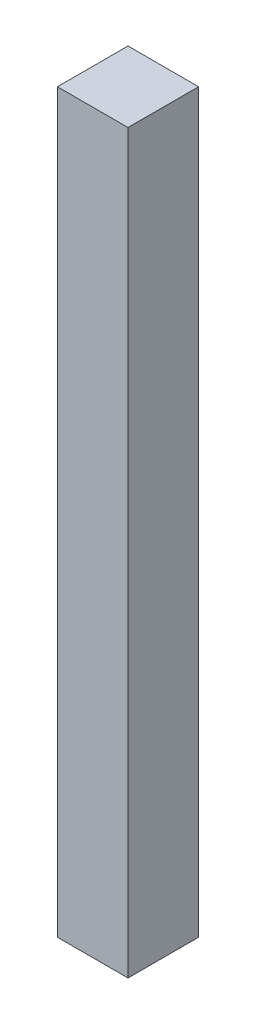
SolidWorks part; units mm, degrees
ref_plane "Front Plane" through (0, 0, 0) normal (0, 0, 1) x (1, 0, 0)
ref_plane "Top Plane" through (0, 0, 0) normal (0, 1, 0) x (1, 0, 0)
ref_plane "Right Plane" through (0, 0, 0) normal (1, 0, 0) x (0, 0, -1)
sketch "Sketch1" plane through (0, -45.0089, 0) normal (0, 1, 0) x (1, 0, 0)
  line L0 (-76.7059, -45.7179) -> (-67.1809, -45.7179) construction
  line L1 (-76.7059, -40.9554) -> (-76.7059, -50.4804) construction
  line L2 (-71.9434, -50.4804) -> (-71.9434, -40.9554) construction
  line L3 (-67.1809, -40.9554) -> (-76.7059, -40.9554) construction
  line L5 (-67.3079, -50.3534) -> (-76.5789, -50.3534)
  line L7 (-67.1809, -50.4804) -> (-67.1809, -40.9554) construction
  line L11 (-76.7059, -50.4804) -> (-67.1809, -50.4804) construction
  line L12 (-67.3079, -50.3534) -> (-67.3079, -41.0824)
  line L13 (-67.3079, -41.0824) -> (-76.5789, -41.0824)
  line L14 (-76.5789, -50.3534) -> (-76.5789, -41.0824)
  line L15 (-67.3079, -50.3534) -> (-76.5789, -41.0824) construction
  line L16 (-67.3079, -41.0824) -> (-76.5789, -50.3534) construction
  point P10 (-71.9434, -45.7179)
  dimension "D1" = 0.127
extrude "Boss-Extrude1" add sketch "Sketch1" along normal up to surface (96.7317 mm away)
